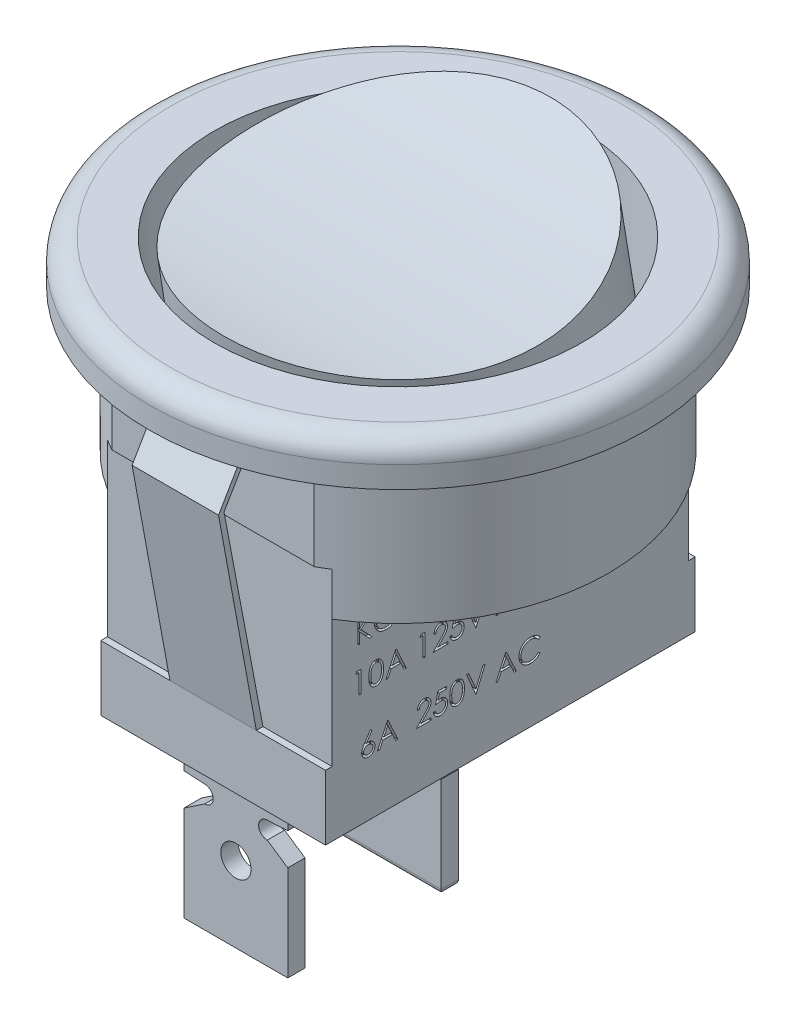
SolidWorks part; units mm, degrees
material "PF"
ref_plane "Front Plane" through (0, 0, 0) normal (0, 0, 1) x (1, 0, 0)
ref_plane "Top Plane" through (0, 0, 0) normal (0, 1, 0) x (1, 0, 0)
ref_plane "Right Plane" through (0, 0, 0) normal (1, 0, 0) x (0, 0, -1)
sketch "Sketch1" plane through (0, 0, 0) normal (0, 1, 0) x (1, 0, 0)
  circle A0 centre (0, 0) radius 11.5
  dimension "D1" = 23
extrude "Boss-Extrude1" add sketch "Sketch1" along normal blind 2
fillet "Fillet1" radius 1 1 edges at (0, 2, 11.5)
sketch "Sketch2" plane through (0, 0, 0) normal (0, -1, 0) x (1, 0, 0)
  line L0 (-9.75, 0) -> (-10.25, 0) construction
  line L1 (-10.25, 0) -> (-10.25, -0.75)
  line L2 (-10.25, 0) -> (-10.25, 0.75)
  line L3 (-10.25, -0.75) -> (-9.7211, -0.75)
  line L4 (-10.25, 0.75) -> (-9.7211, 0.75)
  arc A0 (-9.7211, -0.75) -> (-9.7211, 0.75) centre (0, 0) ccw
  dimension "D1" = 19.5
  dimension "D2" = 0.5
  dimension "D3" = 0.75
  dimension "D4" = 0.75
  dimension "D5" = 0.0289
extrude "Boss-Extrude2" add sketch "Sketch2" along normal blind 6.6
sketch "Sketch3" plane through (0, -6.6, 0) normal (0, -1, 0) x (1, 0, 0)
  line L0 (0, 0) -> (-5.2, 0) construction
  line L1 (0, 0) -> (5.2, 0) construction
  line L2 (-5.2, 0) -> (-5.2, -8.25)
  line L3 (-5.2, 0) -> (-5.2, 8.25)
  line L4 (5.2, 0) -> (5.2, -8.25)
  line L5 (5.2, 0) -> (5.2, 8.25)
  line L6 (-5.2, -8.25) -> (5.2, -8.25)
  line L7 (-5.2, 8.25) -> (5.2, 8.25)
  dimension "D1" = 5.2
  dimension "D2" = 5.2
  dimension "D3" = 8.25
  dimension "D4" = 8.25
  dimension "D5" = 8.25
  dimension "D6" = 8.25
extrude "Boss-Extrude3" add sketch "Sketch3" along normal blind 8.9
sketch "Sketch4" plane through (0, -6.6, 0) normal (0, -1, 0) x (1, 0, 0)
  line L0 (-5.1962, 8.25) -> (5.1962, 8.25) construction
  line L1 (5.1962, -8.25) -> (-5.1962, -8.25) construction
  line L2 (-5.1962, 8.25) -> (5.1962, 8.25)
  line L3 (5.1962, -8.25) -> (-5.1962, -8.25)
  arc A0 (5.1962, 8.25) -> (-5.1962, 8.25) centre (0, 0) ccw construction
  arc A1 (-5.1962, -8.25) -> (5.1962, -8.25) centre (0, 0) ccw construction
  arc A2 (5.1962, 8.25) -> (-5.1962, 8.25) centre (0, 0) ccw
  arc A3 (-5.1962, -8.25) -> (5.1962, -8.25) centre (0, 0) ccw
extrude "Cut-Extrude1" cut sketch "Sketch4" against normal blind 2
sketch "Sketch5" plane through (0, -15.5, 0) normal (0, -1, 0) x (1, 0, 0)
  line L0 (2.4, 7.5) -> (-2.4, 7.5)
  line L1 (2.4, 0.4) -> (-2.4, 0.4)
  line L2 (2.4, 0.4) -> (2.4, -0.4)
  line L3 (2.4, -0.4) -> (-2.4, -0.4)
  line L4 (-2.4, 0.4) -> (-2.4, -0.4)
  line L5 (2.4, 0.4) -> (-2.4, -0.4) construction
  line L6 (2.4, -0.4) -> (-2.4, 0.4) construction
  line L7 (-2.4, 7.5) -> (-2.4, 6.7)
  line L8 (2.4, 6.7) -> (-2.4, 6.7)
  line L9 (2.4, 7.5) -> (2.4, 6.7)
  point P0 (0, 0)
  dimension "D1" = 0.8
  dimension "D2" = 4.8
  dimension "D3" = 2
extrude "Boss-Extrude4" add sketch "Sketch5" along normal blind 7.5 separate body
sketch "Sketch6" plane through (0, 0, 7.5) normal (0, 0, 1) x (1, 0, 0)
  line L0 (2.4, -19.25) -> (-2.4, -19.25)
  line L1 (0, -23) -> (0, -15.5) construction
  line L2 (1.45, -17.7) -> (2.4, -18.3371)
  line L3 (1.45, -16.9) -> (2.4, -16.8485)
  line L4 (2.4, -15.5) -> (-2.4, -15.5)
  line L5 (-2.4, -15.5) -> (-2.4, -23)
  line L6 (-2.4, -23) -> (2.4, -23)
  line L7 (2.4, -23) -> (2.4, -15.5)
  line L9 (-2.4, -15.5) -> (-2.4, -23)
  line L10 (-2.4, -23) -> (2.4, -23)
  line L11 (2.4, -23) -> (2.4, -15.5)
  line L12 (-1.45, -16.9) -> (-2.4, -16.8485)
  line L13 (-1.45, -17.7) -> (-2.4, -18.3371)
  line L18 (2.4, -15.5) -> (-2.4, -15.5)
  circle A0 centre (0, -19.25) radius 0.7011
  arc A1 (1.45, -16.9) -> (1.45, -17.7) centre (1.45, -17.3) ccw
  circle A2 centre (-1.45, -17.3) radius 0.4
  line M11 (2.4, -23) -> (2.4, -15.5)
  dimension "D2" = 1.4022
  dimension "D3" = 0.8
  dimension "D4" = 0.8
  dimension "D6" = 1.45
  dimension "D7" = 1.45
  dimension "D9" = 1.1438
  dimension "D10" = 0.9514
  dimension "D1" = 0
extrude "Cut-Extrude2" cut sketch "Sketch6" against normal up to surface (7.9 mm away) contours L1 A0 L0 | L1 L0 A0 | L0 L1 A0 | A0 L1 L0 | L3 A1 L2 M11 | A2 | A2 L12 L9 L13
chamfer "Chamfer1" distance 0.25 angle 45 4 edges at (0, -23, 6.7) (-2.4, -23, 7.1) (2.4, -23, 7.1) (0, -23, 7.5)
sketch "Sketch7" plane through (0, -4.6, 0) normal (0, -1, 0) x (1, 0, 0)
  line L0 (0, -9.75) -> (0, -8.5545)
  line L1 (0, -8.5545) -> (4.6779, -8.5545)
  line L2 (0, -8.5545) -> (-4.6779, -8.5545)
  arc A0 (-5.1962, -8.25) -> (5.1962, -8.25) centre (0, 0) ccw construction
  arc A1 (-9.7211, -0.75) -> (-9.7211, 0.75) centre (0, 0) ccw construction
  arc A2 (-9.7211, -0.75) -> (-9.7211, 0.75) centre (0, 0) ccw
  arc M2 (-5.1962, -8.25) -> (5.1962, -8.25) centre (0, 0) ccw
  dimension "D1" = 4.6779
extrude "Cut-Extrude3" cut sketch "Sketch7" against normal blind 4.6 contours L1 L0 M2 | L0 L2 M2
mirror "Mirror1" about plane through (0, 0, 0) normal (0, 0, 1) of "Cut-Extrude3"
sketch "Sketch8" plane through (0, -15.5, 0) normal (0, -1, 0) x (1, 0, 0)
  line L0 (-4.6779, -8.5545) -> (4.6779, -8.5545) construction
  line L1 (-4.6779, 8.5545) -> (4.6779, 8.5545) construction
  line L2 (-4.6779, -8.5545) -> (4.6779, -8.5545)
  line L3 (-4.6779, 8.5545) -> (4.6779, 8.5545)
  line L4 (-5.2, 8.25) -> (-5.2, -8.25)
  line L5 (-5.2, -8.25) -> (5.2, -8.25)
  line L6 (5.2, -8.25) -> (5.2, 8.25)
  line L7 (5.2, 8.25) -> (-5.2, 8.25)
  line L8 (-5.2, 8.25) -> (-5.2, -8.25)
  line L9 (-5.2, -8.25) -> (5.2, -8.25)
  line L10 (5.2, -8.25) -> (5.2, 8.25)
  line L11 (5.2, 8.25) -> (-5.2, 8.25)
  line L12 (-5.2, 8.25) -> (-5.2, 8.5545)
  line L13 (-5.2, 8.5545) -> (-4.6779, 8.5545)
  line L14 (5.2, 8.25) -> (5.2, 8.5545)
  line L15 (5.2, 8.5545) -> (4.6779, 8.5545)
  line L16 (4.6779, -8.5545) -> (5.2, -8.5545)
  line L17 (5.2, -8.5545) -> (5.2, -8.25)
  line L18 (-5.2, -8.25) -> (-5.2, -8.5545)
  line L19 (-5.2, -8.5545) -> (-4.6779, -8.5545)
  line M10 (-5.2, -8.25) -> (5.2, -8.25)
  line M12 (5.2, 8.25) -> (-5.2, 8.25)
  dimension "D1" = 0
extrude "Boss-Extrude5" add sketch "Sketch8" against normal blind 3 contours L18 L19 L2 L16 L17 M10 | L14 L15 L3 L13 L12 M12
sketch "Sketch10" plane through (0, 2, 0) normal (0, 1, 0) x (1, 0, 0)
  circle A0 centre (0, 0) radius 8.5
  dimension "D1" = 17
extrude "Cut-Extrude4" cut sketch "Sketch10" against normal blind 6
sketch "Sketch11" plane through (-10.25, 0, 0) normal (-1, 0, 0) x (0, 0, 1)
  line L4 (0.75, 0) -> (-0.75, 0)
  line L5 (-0.75, 0) -> (-0.75, -6.6)
  line L6 (-0.75, -6.6) -> (0.75, -6.6)
  line L7 (0.75, -6.6) -> (0.75, 0)
  line L8 (0.75, 0) -> (-0.75, 0)
  line L9 (-0.75, 0) -> (-0.75, -6.6)
  line L11 (0.75, -6.6) -> (0.75, 0)
  line L13 (-0.75, -6.6) -> (0.75, -6.6)
  circle A0 centre (0, -0.74) radius 0.74
  dimension "D2" = 1.48
  dimension "D1" = 0
extrude "Cut-Extrude8" cut sketch "Sketch11" against normal through all contours A0
sketch "Sketch12" plane through (0, 0, 0) normal (1, 0, 0) x (0, 0, -1)
  line L0 (-8.5, 2) -> (8.4651, 4.7726)
  line L1 (8.5, 2) -> (-8.5, 2) construction
  line L2 (10.5, 2) -> (-10.5, 2) construction
ref_plane "Plane1" through (0, 3.301, 0.5395) normal (0, -0.9869, -0.1613) x (0, 0.1613, -0.9869)
sketch "Sketch14" plane through (0, 3.301, 0.5395) normal (0, -0.9869, -0.1613) x (0, 0.1613, -0.9869)
  circle A0 centre (0, 0) radius 7.6258
extrude "Boss-Extrude6" add sketch "Sketch14" along normal blind 6 separate body
sketch "Sketch15" plane through (0, 0, 0) normal (1, 0, 0) x (0, 0, -1)
  line L0 (-8.2476, -6.6) -> (8.2476, -6.6) construction
  circle A0 centre (-4.313, 31.7) radius 29.8806
  dimension "D1" = 38.3
extrude "Cut-Extrude9" cut sketch "Sketch15" along normal through all and the other way through all
sketch "Sketch16" plane through (5.2, 0, 0) normal (1, 0, 0) x (0, 0, -1)
  text T0 "KCD1" font "Century Gothic" height 1
extrude "Cut-Extrude10" cut sketch "Sketch16" against normal blind 0.2
fillet "Fillet2" radius 0.25 4 edges at (-2.4, -23, 0) (0, -23, 0.4) (2.4, -23, 0) (0, -23, -0.4)
sketch "Sketch17" plane through (5.2, 0, 0) normal (1, 0, 0) x (0, 0, -1)
  text T0 "10A 125V AC\r\n 6A  250V AC" font "Century Gothic" height 1
extrude "Cut-Extrude11" cut sketch "Sketch17" against normal blind 0.2
sketch "Sketch18" plane through (0, 0, 0) normal (1, 0, 0) x (0, 0, -1)
  line L0 (-8.5545, 0) -> (-8.5545, -3)
  line L1 (-8.5545, 0) -> (-8.5545, -4.6) construction
  line L2 (-8.5545, -3) -> (-10.3045, -3)
  line L3 (8.5545, 0) -> (8.5545, -3)
  line L4 (8.5545, 0) -> (8.5545, -4.6) construction
  line L5 (8.5545, -3) -> (10.3045, -3)
  line L6 (-8.5545, 0) -> (-10.3045, -3)
  line L7 (8.5545, 0) -> (10.3045, -3)
  line L8 (-10.3045, -3) -> (-8.5545, -12.5)
  line L9 (10.3045, -3) -> (8.5545, -12.5)
  line L10 (-8.25, -12.5) -> (-10.0515, -3)
  line L11 (-10.0515, -3) -> (-8.5545, -0.4643)
  line L12 (8.25, -12.5) -> (9.9486, -3)
  line L13 (9.9486, -3) -> (8.5545, -0.5811)
  line L14 (-8.5545, -12.5) -> (-8.25, -12.5)
  line L15 (8.25, -12.5) -> (8.5545, -12.5)
  dimension "D1" = 1.75
  dimension "D2" = 3
  dimension "D3" = 3
  dimension "D4" = 1.75
  dimension "D5" = 0.3
  dimension "D6" = 0.3
  dimension "D7" = 0.3
  dimension "D8" = 0.3
extrude "Boss-Extrude7" add sketch "Sketch18" along normal blind 2 and the other way blind 2 contours L2 L11 L0 L6 | L8 L14 L10 L2 | L13 L5 L7 L3 | L12 L15 L9 L5
